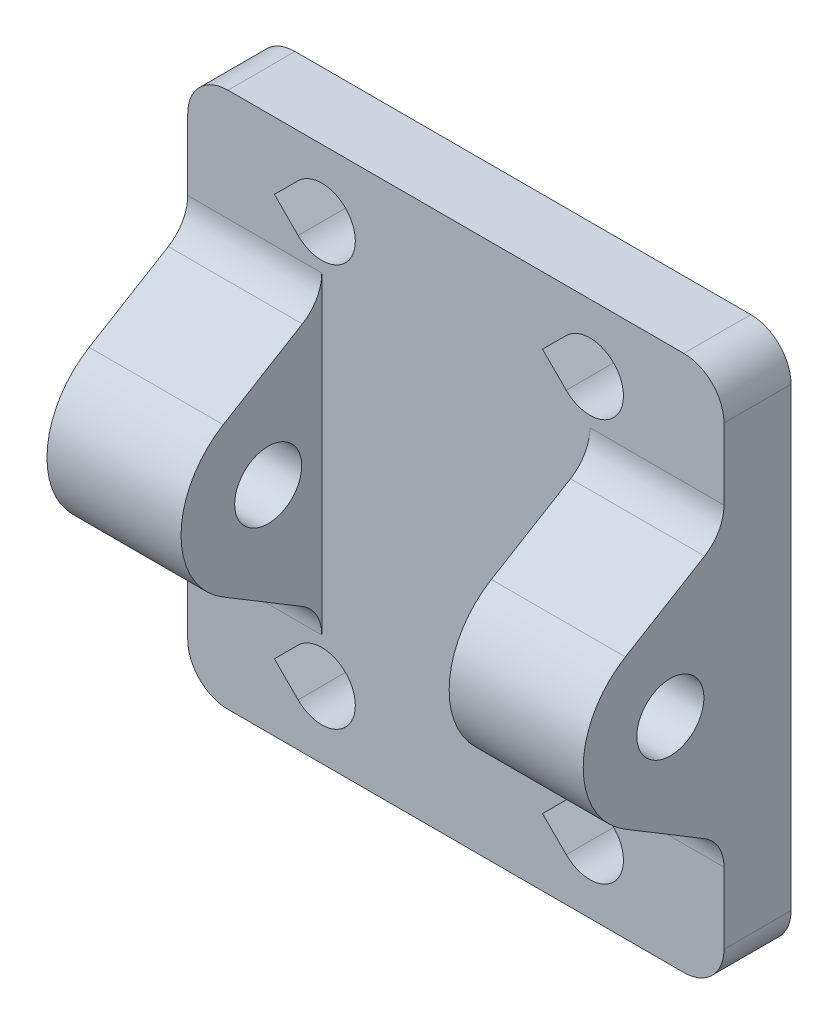
SolidWorks part; units mm, degrees
ref_plane "Front Plane" through (0, 0, 0) normal (0, 0, 1) x (1, 0, 0)
ref_plane "Top Plane" through (0, 0, 0) normal (0, 1, 0) x (1, 0, 0)
ref_plane "Right Plane" through (0, 0, 0) normal (1, 0, 0) x (0, 0, -1)
sketch "Sketch1" plane through (0, 0, 0) normal (0, 0, 1) x (1, 0, 0)
  line L1 (0, 0) -> (40, 0)
  line L2 (0, 0) -> (0, 40)
  line L3 (0, 40) -> (40, 40)
  line L4 (40, 0) -> (40, 40)
  dimension "D1" = 40
  dimension "D2" = 40
extrude "Boss-Extrude1" add sketch "Sketch1" along normal blind 5
sketch "Sketch2" plane through (0, 0, 5) normal (0, 0, 1) x (1, 0, 0)
  line L0 (0, 40) -> (0, 0) construction
  line L1 (40, 0) -> (40, 40) construction
  line L2 (40, 40) -> (0, 40) construction
  line L3 (0, 0) -> (40, 0) construction
  line L4 (8.2322, 36.7678) -> (6.4645, 35)
  line L5 (6.4645, 35) -> (8.2322, 33.2322)
  line L6 (8.2322, 33.2322) -> (8.2322, 36.7678) construction
  line L7 (26.4645, 35) -> (28.2322, 33.2322)
  line L8 (28.2322, 36.7678) -> (26.4645, 35)
  line L9 (26.4645, 5) -> (28.2322, 3.2322)
  line L10 (28.2322, 6.7678) -> (26.4645, 5)
  line L11 (6.4645, 5) -> (8.2322, 3.2322)
  line L12 (8.2322, 6.7678) -> (6.4645, 5)
  arc A0 (8.2322, 33.2322) -> (8.2322, 36.7678) centre (10, 35) ccw
  arc A1 (28.2322, 33.2322) -> (28.2322, 36.7678) centre (30, 35) ccw
  arc A2 (8.2322, 3.2322) -> (8.2322, 6.7678) centre (10, 5) ccw
  arc A3 (28.2322, 3.2322) -> (28.2322, 6.7678) centre (30, 5) ccw
  point P1 (0, 0)
  point P3 (0, 0)
  dimension "D1" = 5
  dimension "D2" = 10
  dimension "D3" = 10
  dimension "D5" = 5
  dimension "D6" = 5
  dimension "D7" = 45
  dimension "D8" = 2
  dimension "D9" = 2
extrude "Cut-Extrude1" cut sketch "Sketch2" against normal through all
sketch "Sketch3" plane through (0, 0, 0) normal (-1, 0, 0) x (0, 0, 1)
  line L0 (5, 40) -> (5, 0) construction
  line L1 (5, 40) -> (0, 40) construction
  line L2 (12.3552, 25.5671) -> (5, 30)
  line L3 (12.3552, 14.4329) -> (5, 10)
  line L4 (5, 30) -> (5, 10)
  circle A0 centre (9, 20) radius 2.5
  arc A1 (12.3552, 14.4329) -> (12.3552, 25.5671) centre (9, 20) ccw
  circle A2 centre (9, 20) radius 6.5 construction
  dimension "D1" = 5
  dimension "D2" = 4
  dimension "D3" = 20
  dimension "D5" = 10
  dimension "D6" = 10
  dimension "D4" = 4
extrude "Boss-Extrude2" add sketch "Sketch3" against normal blind 10
fillet "Fillet1" radius 3 2 edges at (5, 10, 5) (5, 30, 5)
pattern_linear "LPattern1" count 2 spacing 30 along (1, 0, 0) of "Boss-Extrude2", "Fillet1"
fillet "Fillet2" radius 3 4 edges at (0, 0, 2.5) (40, 0, 2.5) (40, 40, 2.5) (0, 40, 2.5)
